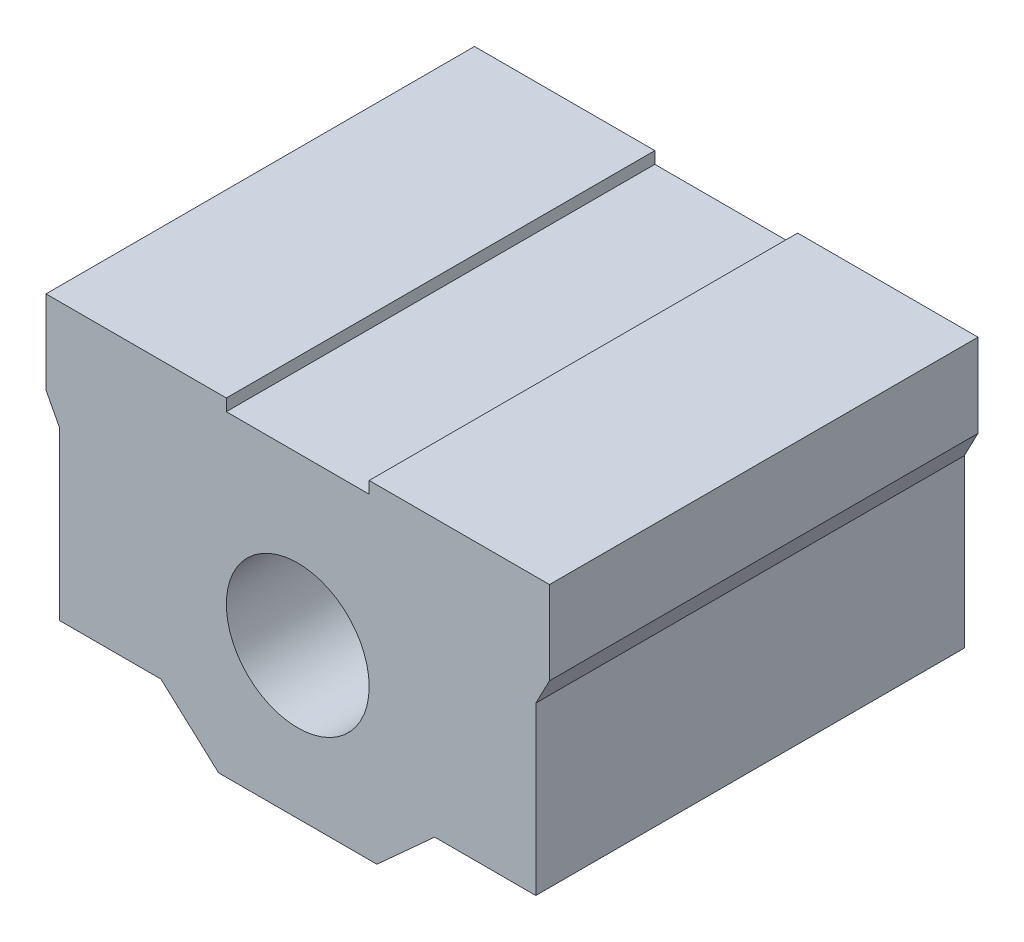
SolidWorks part; units mm, degrees
ref_plane "前视基准面" through (0, 0, 0) normal (0, 0, 1) x (1, 0, 0)
ref_plane "上视基准面" through (0, 0, 0) normal (0, 1, 0) x (1, 0, 0)
ref_plane "右视基准面" through (0, 0, 0) normal (1, 0, 0) x (0, 0, -1)
sketch "草图1" plane through (0, 0, 0) normal (0, 0, 1) x (1, 0, 0)
  line L0 (0, 42.0934) -> (0, 0) construction
  line L1 (0, 0) -> (49.8045, 0) construction
  line L2 (6.65, 0) -> (-6.65, 0)
  line L3 (-6.65, 0) -> (-11.5, 4.4)
  line L4 (-11.5, 4.4) -> (-20, 4.4)
  line L5 (-20, 4.4) -> (-20, 18.4)
  line L6 (-20, 18.4) -> (-21.15, 20.6)
  line L7 (-21.15, 20.6) -> (-21.15, 27.6)
  line L8 (-21.15, 27.6) -> (-6, 27.6)
  line L9 (-6, 27.6) -> (-6, 26.6)
  line L10 (-6, 26.6) -> (6, 26.6)
  line L11 (11.5, 4.4) -> (20, 4.4)
  line L12 (6.65, 0) -> (11.5, 4.4)
  line L13 (20, 18.4) -> (21.15, 20.6)
  line L14 (20, 4.4) -> (20, 18.4)
  line L15 (21.15, 20.6) -> (21.15, 27.6)
  line L16 (6, 27.6) -> (6, 26.6)
  line L17 (21.15, 27.6) -> (6, 27.6)
  circle A0 centre (0, 12.6) radius 6
  point P23 (0, 26.6)
  dimension "D1" = 12
  dimension "D2" = 42.3
  dimension "D3" = 27.6
  dimension "D4" = 12.6
  dimension "D5" = 40
  dimension "D6" = 13.3
  dimension "D7" = 12
  dimension "D8" = 1
  dimension "D9" = 23.2
  dimension "D10" = 8.5
  dimension "D11" = 14
  dimension "D12" = 7
extrude "凸台-拉伸1" add sketch "草图1" along normal blind 36
